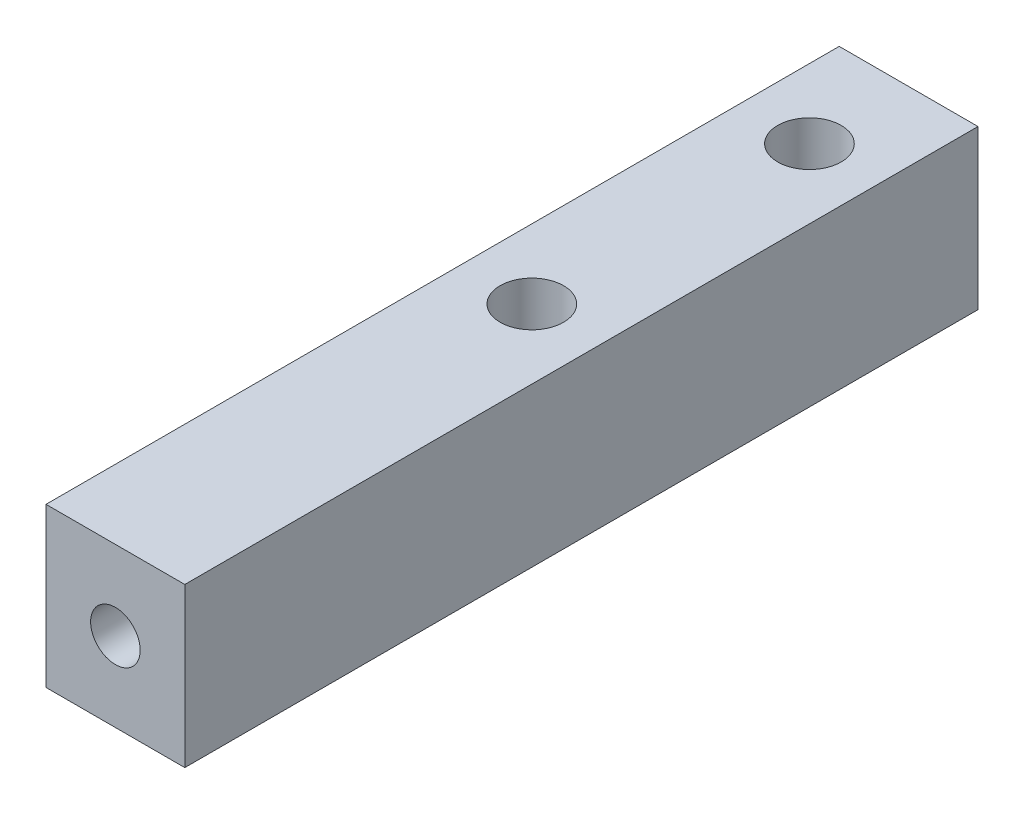
SolidWorks part; units mm, degrees
material "AISI 304"
ref_plane "Plan de face" through (0, 0, 0) normal (0, 0, 1) x (1, 0, 0)
ref_plane "Plan de dessus" through (0, 0, 0) normal (0, 1, 0) x (1, 0, 0)
ref_plane "Plan de droite" through (0, 0, 0) normal (1, 0, 0) x (0, 0, -1)
sketch "Esquisse1" plane through (0, 0, 0) normal (0, 0, 1) x (1, 0, 0)
  line L1 (0, 0) -> (7, 0)
  line L2 (0, 0) -> (0, 8)
  line L3 (0, 8) -> (7, 8)
  line L4 (7, 0) -> (7, 8)
  dimension "D1" = 8
  dimension "D2" = 7
extrude "Boss.-Extru.1" add sketch "Esquisse1" along normal blind 40
hole_wizard "Trou pour taraudage pour trou taraudé M31" positions "Esquisse2" profile "Esquisse3" hole size "M3" standard "ISO"
sketch "Esquisse2" plane through (0, 0, 40) normal (0, 0, 1) x (1, 0, 0)
  line L0 (7, 8) -> (0, 8) construction
  line L1 (3.5, 5.6129) -> (3.5, 2.0909) construction
  line L3 (7, 0) -> (7, 8) construction
  line L4 (0, 8) -> (0, 0) construction
  point P0 (3.5, 4)
  point P5 (3.5, 8)
  dimension "D1" = 4
sketch "Esquisse3" plane through (3.5, 4, 40) normal (1, 0, 0) x (0, -1, 0)
  line L0 (0, 0) -> (0, 30.7511)
  line L1 (0, 30.7511) -> (1.25, 30)
  line L2 (1.25, 30) -> (1.25, 0)
  line L5 (1.25, 0) -> (0, 0)
  line L10 (0, 30.7511) -> (-1.25, 30) construction
  line L11 (0, -6.35) -> (0, 107.95) construction
  dimension "Diamètre du perçage" = 2.5
  dimension "Profondeur du perçage" = 30
  dimension "Angle de pointe" = 118
sketch "Esquisse4" plane through (0, 8, 0) normal (0, 1, 0) x (1, 0, 0)
  line L0 (7, -40) -> (0, -40) construction
  line L2 (3.5, -19) -> (3.5, -5) construction
  line L3 (7, -40) -> (7, 0) construction
  line L4 (0, -40) -> (0, 0) construction
  circle A0 centre (3.5, -5) radius 1.6
  circle A1 centre (3.5, -19) radius 1.6
  dimension "D1" = 3.2
  dimension "D2" = 3.2
  dimension "D3" = 14
  dimension "D4" = 35
extrude "Enlèv. mat.-Extru.1" cut sketch "Esquisse4" against normal through all
